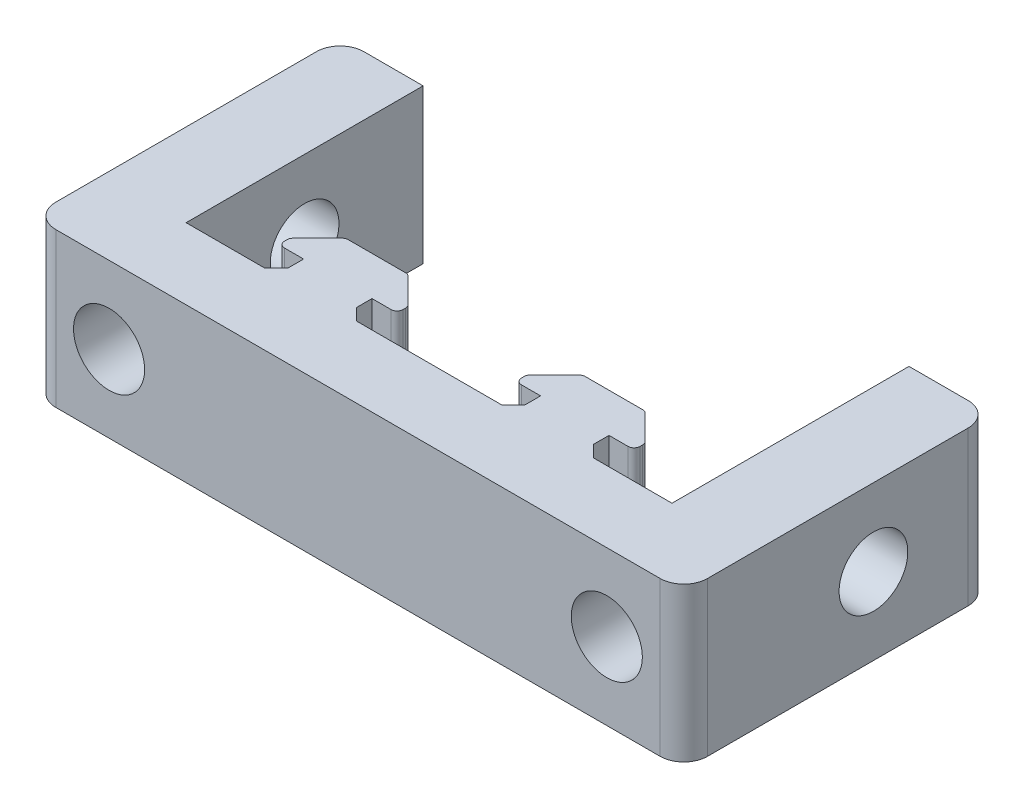
SolidWorks part; units mm, degrees
ref_plane "Front Plane" through (0, 0, 0) normal (0, 0, 1) x (1, 0, 0)
ref_plane "Top Plane" through (0, 0, 0) normal (0, 1, 0) x (1, 0, 0)
ref_plane "Right Plane" through (0, 0, 0) normal (1, 0, 0) x (0, 0, -1)
sketch "Sketch1" plane through (0, 0, 0) normal (0, 0, 1) x (1, 0, 0)
  line L5 (-27.5, -6.5) -> (27.5, -6.5)
  line L6 (-27.5, -6.5) -> (-27.5, 6.5)
  line L7 (-27.5, 6.5) -> (27.5, 6.5)
  line L8 (27.5, -6.5) -> (27.5, 6.5)
  line L9 (-27.5, -6.5) -> (27.5, 6.5) construction
  line L10 (-27.5, 6.5) -> (27.5, -6.5) construction
  point P0 (0, 0)
  dimension "D1" = 13
  dimension "D2" = 55
extrude "Boss-Extrude1" add sketch "Sketch1" along normal blind 10
sketch "Sketch2" plane through (0, 0, 10) normal (0, 0, 1) x (1, 0, 0)
  line L0 (27.5, -6.5) -> (27.5, 6.5) construction
  line L1 (-27.5, -6.5) -> (27.5, -6.5)
  line L2 (-27.5, -6.5) -> (-27.5, 6.5)
  line L3 (-27.5, 6.5) -> (27.5, 6.5)
  line L4 (27.5, -6.5) -> (27.5, 6.5)
  line L5 (-27.5, -6.5) -> (27.5, 6.5) construction
  line L6 (-27.5, 6.5) -> (27.5, -6.5) construction
  line L7 (-27.5, -6.5) -> (27.5, -6.5) construction
  point P0 (0, 0)
extrude "Cut-Extrude1" cut sketch "Sketch2" against normal offset from surface (4 mm away) 6 contours L3 L4 L1 L2 up to face at (0, 0, 0)
sketch "Sketch4" plane through (0, 0, 6) normal (0, 0, 1) x (1, 0, 0)
  line L0 (21, 0) -> (-21, 0) construction
  circle A0 centre (21, 0) radius 3
  circle A1 centre (-21, 0) radius 3
  point P4 (0, 0)
  dimension "D2" = 6
  dimension "D1" = 42
extrude "Cut-Extrude2" cut sketch "Sketch4" against normal up to next
sketch "Sketch5" plane through (0, 6.5, 0) normal (0, 1, 0) x (1, 0, 0)
  line L1 (9.9, 5.5995) -> (12.6324, 5.5995)
  line L2 (12.6324, 5.5995) -> (15, 3.2319)
  line L3 (15, 3.2319) -> (15, 2.3)
  line L4 (15, 2.3) -> (12.8865, 2.3)
  line L5 (12.8865, 2.3) -> (12.8865, 0.9829)
  line L6 (12.8865, 0.9829) -> (13.8694, 0)
  line L7 (6.1306, 0) -> (7.1135, 0.9829)
  line L8 (7.1135, 0.9829) -> (7.1135, 2.3)
  line L9 (7.1135, 2.3) -> (5, 2.3)
  line L10 (5, 2.3) -> (5, 3.2319)
  line L11 (5, 3.2319) -> (7.3676, 5.5995)
  line L12 (7.3676, 5.5995) -> (9.9, 5.5995)
  line L14 (10.1, 5.5995) -> (12.6324, 5.5995) construction
  line L17 (13.8694, 0) -> (6.1306, 0)
  line L18 (12.8865, 0.9829) -> (14.0205, -0.1511) construction
  line L19 (5.9795, -0.1511) -> (7.1135, 0.9829) construction
  line L313 (0, 1.8) -> (0, 0)
  line L314 (0, 0) -> (5.1372, 0)
  line L315 (5.6259, 0.2024) -> (6.6135, 1.19)
  line L316 (6.6135, 1.19) -> (6.6135, 1.8)
  line L317 (6.6135, 1.8) -> (4.5, 1.8)
  line L318 (4.5, 1.8) -> (4.5, 3.439)
  line L319 (4.5, 3.439) -> (7.1605, 6.0995)
  line L320 (7.1605, 6.0995) -> (9.9, 6.0995)
  line L321 (9.9, 6.0995) -> (10, 6.1995)
  line L322 (10, 6.1995) -> (10.1, 6.0995)
  line L323 (10.1, 6.0995) -> (12.8395, 6.0995)
  line L324 (12.8395, 6.0995) -> (15.5, 3.439)
  line L325 (15.5, 3.439) -> (15.5, 1.8)
  line L326 (15.5, 1.8) -> (13.3865, 1.8)
  line L327 (13.3865, 1.8) -> (13.3865, 1.19)
  line L328 (13.3865, 1.19) -> (14.3741, 0.2024)
  line L329 (14.8628, 0) -> (18.5, 0)
  line L330 (20, 1.5) -> (20, 5.1372)
  line L331 (19.7976, 5.6259) -> (18.81, 6.6135)
  line L332 (18.81, 6.6135) -> (18.2, 6.6135)
  line L333 (18.2, 6.6135) -> (18.2, 4.5)
  line L334 (18.2, 4.5) -> (16.561, 4.5)
  line L335 (16.561, 4.5) -> (13.9005, 7.1605)
  line L336 (13.9005, 7.1605) -> (13.9005, 9.9)
  line L337 (13.9005, 9.9) -> (13.8005, 10)
  line L338 (13.8005, 10) -> (13.9005, 10.1)
  line L339 (13.9005, 10.1) -> (13.9005, 12.8395)
  line L340 (13.9005, 12.8395) -> (16.561, 15.5)
  line L341 (16.561, 15.5) -> (18.2, 15.5)
  line L342 (18.2, 15.5) -> (18.2, 13.3865)
  line L343 (18.2, 13.3865) -> (18.81, 13.3865)
  line L344 (18.81, 13.3865) -> (19.7976, 14.3741)
  line L345 (20, 14.8628) -> (20, 18.5)
  line L346 (18.5, 20) -> (14.8628, 20)
  line L347 (14.3741, 19.7976) -> (13.3865, 18.81)
  line L348 (13.3865, 18.81) -> (13.3865, 18.2)
  line L349 (13.3865, 18.2) -> (15.5, 18.2)
  line L350 (15.5, 18.2) -> (15.5, 16.561)
  line L351 (15.5, 16.561) -> (12.8395, 13.9005)
  line L352 (12.8395, 13.9005) -> (10.1, 13.9005)
  line L353 (10.1, 13.9005) -> (10, 13.8005)
  line L354 (10, 13.8005) -> (9.9, 13.9005)
  line L355 (9.9, 13.9005) -> (7.1605, 13.9005)
  line L356 (7.1605, 13.9005) -> (4.5, 16.561)
  line L357 (4.5, 16.561) -> (4.5, 18.2)
  line L358 (4.5, 18.2) -> (6.6135, 18.2)
  line L359 (6.6135, 18.2) -> (6.6135, 18.81)
  line L360 (6.6135, 18.81) -> (5.6259, 19.7976)
  line L361 (5.1372, 20) -> (0, 20)
  line L362 (0, 20) -> (0, 18.2)
  line L363 (0, 18.2) -> (2.7, 18.2)
  line L364 (2.7, 18.2) -> (2.7, 16.239)
  line L365 (2.7, 16.239) -> (6.0995, 12.8395)
  line L366 (6.0995, 12.8395) -> (6.0995, 10.1)
  line L367 (6.0995, 10.1) -> (6.1995, 10)
  line L368 (6.1995, 10) -> (6.0995, 9.9)
  line L369 (6.0995, 9.9) -> (6.0995, 7.1605)
  line L370 (6.0995, 7.1605) -> (2.7, 3.761)
  line L371 (2.7, 3.761) -> (2.7, 1.8)
  line L372 (2.7, 1.8) -> (0, 1.8)
  line L373 (0, 1.8) -> (0, 0) construction
  line L374 (0, 0) -> (5.1372, 0) construction
  line L375 (5.6259, 0.2024) -> (6.6135, 1.19) construction
  line L376 (6.6135, 1.19) -> (6.6135, 1.8) construction
  line L377 (6.6135, 1.8) -> (4.5, 1.8) construction
  line L378 (4.5, 1.8) -> (4.5, 3.439) construction
  line L379 (4.5, 3.439) -> (7.1605, 6.0995) construction
  line L380 (7.1605, 6.0995) -> (9.9, 6.0995) construction
  line L381 (9.9, 6.0995) -> (10, 6.1995) construction
  line L382 (10, 6.1995) -> (10.1, 6.0995) construction
  line L383 (10.1, 6.0995) -> (12.8395, 6.0995) construction
  line L384 (12.8395, 6.0995) -> (15.5, 3.439) construction
  line L385 (15.5, 3.439) -> (15.5, 1.8) construction
  line L386 (15.5, 1.8) -> (13.3865, 1.8) construction
  line L387 (13.3865, 1.8) -> (13.3865, 1.19) construction
  line L388 (13.3865, 1.19) -> (14.3741, 0.2024) construction
  line L389 (14.8628, 0) -> (18.5, 0) construction
  line L390 (20, 1.5) -> (20, 5.1372) construction
  line L391 (19.7976, 5.6259) -> (18.81, 6.6135) construction
  line L392 (18.81, 6.6135) -> (18.2, 6.6135) construction
  line L393 (18.2, 6.6135) -> (18.2, 4.5) construction
  line L394 (18.2, 4.5) -> (16.561, 4.5) construction
  line L395 (16.561, 4.5) -> (13.9005, 7.1605) construction
  line L396 (13.9005, 7.1605) -> (13.9005, 9.9) construction
  line L397 (13.9005, 9.9) -> (13.8005, 10) construction
  line L398 (13.8005, 10) -> (13.9005, 10.1) construction
  line L399 (13.9005, 10.1) -> (13.9005, 12.8395) construction
  line L400 (13.9005, 12.8395) -> (16.561, 15.5) construction
  line L401 (16.561, 15.5) -> (18.2, 15.5) construction
  line L402 (18.2, 15.5) -> (18.2, 13.3865) construction
  line L403 (18.2, 13.3865) -> (18.81, 13.3865) construction
  line L404 (18.81, 13.3865) -> (19.7976, 14.3741) construction
  line L405 (20, 14.8628) -> (20, 18.5) construction
  line L406 (18.5, 20) -> (14.8628, 20) construction
  line L407 (14.3741, 19.7976) -> (13.3865, 18.81) construction
  line L408 (13.3865, 18.81) -> (13.3865, 18.2) construction
  line L409 (13.3865, 18.2) -> (15.5, 18.2) construction
  line L410 (15.5, 18.2) -> (15.5, 16.561) construction
  line L411 (15.5, 16.561) -> (12.8395, 13.9005) construction
  line L412 (12.8395, 13.9005) -> (10.1, 13.9005) construction
  line L413 (10.1, 13.9005) -> (10, 13.8005) construction
  line L414 (10, 13.8005) -> (9.9, 13.9005) construction
  line L415 (9.9, 13.9005) -> (7.1605, 13.9005) construction
  line L416 (7.1605, 13.9005) -> (4.5, 16.561) construction
  line L417 (4.5, 16.561) -> (4.5, 18.2) construction
  line L418 (4.5, 18.2) -> (6.6135, 18.2) construction
  line L419 (6.6135, 18.2) -> (6.6135, 18.81) construction
  line L420 (6.6135, 18.81) -> (5.6259, 19.7976) construction
  line L421 (5.1372, 20) -> (0, 20) construction
  line L422 (0, 20) -> (0, 18.2) construction
  line L423 (0, 18.2) -> (2.7, 18.2) construction
  line L424 (2.7, 18.2) -> (2.7, 16.239) construction
  line L425 (2.7, 16.239) -> (6.0995, 12.8395) construction
  line L426 (6.0995, 12.8395) -> (6.0995, 10.1) construction
  line L427 (6.0995, 10.1) -> (6.1995, 10) construction
  line L428 (6.1995, 10) -> (6.0995, 9.9) construction
  line L429 (6.0995, 9.9) -> (6.0995, 7.1605) construction
  line L430 (6.0995, 7.1605) -> (2.7, 3.761) construction
  line L431 (2.7, 3.761) -> (2.7, 1.8) construction
  line L432 (2.7, 1.8) -> (0, 1.8) construction
  arc A45 (5.1372, 0) -> (5.6259, 0.2024) centre (5.1372, 0.6912) ccw
  arc A46 (14.3741, 0.2024) -> (14.8628, 0) centre (14.8628, 0.6912) ccw
  arc A47 (18.5, 0) -> (20, 1.5) centre (18.5, 1.5) ccw
  arc A48 (20, 5.1372) -> (19.7976, 5.6259) centre (19.3088, 5.1372) ccw
  arc A49 (19.7976, 14.3741) -> (20, 14.8628) centre (19.3088, 14.8628) ccw
  arc A50 (20, 18.5) -> (18.5, 20) centre (18.5, 18.5) ccw
  arc A51 (14.8628, 20) -> (14.3741, 19.7976) centre (14.8628, 19.3088) ccw
  arc A52 (5.6259, 19.7976) -> (5.1372, 20) centre (5.1372, 19.3088) ccw
  arc A53 (5.1372, 0) -> (5.6259, 0.2024) centre (5.1372, 0.6912) ccw construction
  arc A54 (14.3741, 0.2024) -> (14.8628, 0) centre (14.8628, 0.6912) ccw construction
  arc A55 (18.5, 0) -> (20, 1.5) centre (18.5, 1.5) ccw construction
  arc A56 (20, 5.1372) -> (19.7976, 5.6259) centre (19.3088, 5.1372) ccw construction
  arc A57 (19.7976, 14.3741) -> (20, 14.8628) centre (19.3088, 14.8628) ccw construction
  arc A58 (20, 18.5) -> (18.5, 20) centre (18.5, 18.5) ccw construction
  arc A59 (14.8628, 20) -> (14.3741, 19.7976) centre (14.8628, 19.3088) ccw construction
  arc A60 (5.6259, 19.7976) -> (5.1372, 20) centre (5.1372, 19.3088) ccw construction
  arc A61 (5.1372, -0.5) -> (5.9795, -0.1511) centre (5.1372, 0.6912) ccw construction
  arc A62 (14.0205, -0.1511) -> (14.8628, -0.5) centre (14.8628, 0.6912) ccw construction
  dimension "D1" = 0
  dimension "D2" = 0.5
extrude "Boss-Extrude3" add sketch "Sketch5" against normal up to surface (13 mm away) up to face at (0, -6.5, 3)
mirror "Mirror1" about plane through (0, 0, 0) normal (1, 0, 0) of "Boss-Extrude3"
sketch "Sketch6" plane through (0, 0, 0) normal (0, 0, -1) x (-1, 0, 0)
  line L0 (13.8694, 6.5) -> (27.5, 6.5) construction
  line L1 (27.5, -6.5) -> (20.5, -6.5)
  line L2 (27.5, -6.5) -> (27.5, 6.5)
  line L3 (27.5, 6.5) -> (20.5, 6.5)
  line L4 (20.5, -6.5) -> (20.5, 6.5)
  line L5 (-27.5, 6.5) -> (-13.8694, 6.5) construction
  line L6 (-27.5, -6.5) -> (-20.5, -6.5)
  line L7 (-27.5, -6.5) -> (-27.5, 6.5)
  line L8 (-27.5, 6.5) -> (-20.5, 6.5)
  line L9 (-20.5, -6.5) -> (-20.5, 6.5)
  dimension "D1" = 41
extrude "Boss-Extrude4" add sketch "Sketch6" along normal blind 20
sketch "Sketch7" plane through (-27.5, 0, 0) normal (-1, 0, 0) x (0, 0, 1)
  line L0 (-20, 0) -> (-10, 0) construction
  line L1 (-20, -6.5) -> (-20, 6.5) construction
  dimension "D1" = 10
hole_wizard "M5 Clearance Hole1" positions "3DSketch1" profile "Sketch8" hole size "M5" standard "ANSI Metric" end condition through all
sketch3d "3DSketch1"
  point P0 (-27.5, 0, -10)
sketch "Sketch8" plane through (-27.5, 0, -10) normal (0, 1, 0) x (0, 0, 1)
  line L0 (0, 0) -> (0, 55)
  line L1 (0, 55) -> (2.9, 55)
  line L2 (2.9, 55) -> (2.9, 0)
  line L5 (2.9, 0) -> (0, 0)
  line L11 (0, -6.35) -> (0, 107.95) construction
  dimension "Thru Hole Dia." = 5.8
  dimension "Thru Hole Depth" = 55
fillet "Fillet1" radius 2 4 edges at (-27.5, 0, 6) (27.5, 0, 6) (-27.5, 0, -20) (27.5, 0, -20)
fillet "Fillet2" radius 0.5 12 edges at (5, 0, -2.3) (15, 0, -2.3) (5, 0, -3.2319) (15, 0, -3.2319) (12.6324, 0, -5.5995) (7.3676, 0, -5.5995) (-12.6324, 0, -5.5995) (-7.3676, 0, -5.5995) (-5, 0, -3.2319) (-5, 0, -2.3) (-15, 0, -3.2319) (-15, 0, -2.3)
